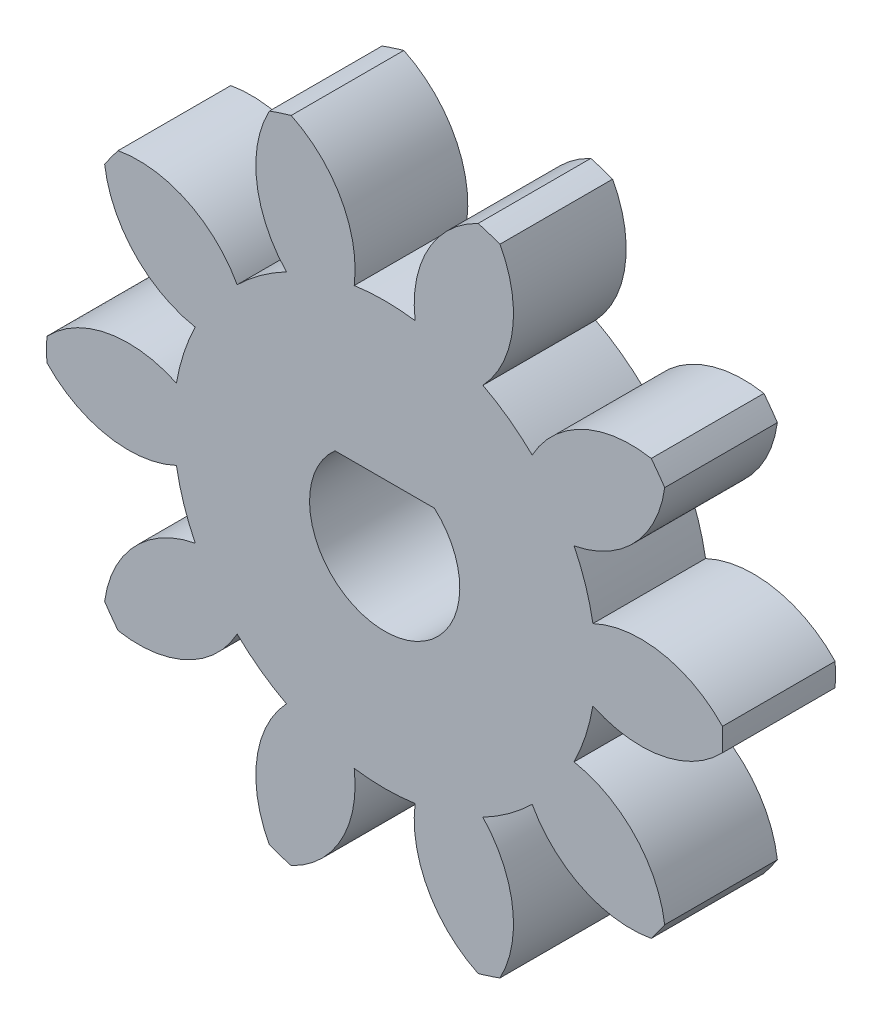
SolidWorks part; units mm, degrees
ref_plane "Front Plane" through (0, 0, 0) normal (0, 0, 1) x (1, 0, 0)
ref_plane "Top Plane" through (0, 0, 0) normal (0, 1, 0) x (1, 0, 0)
ref_plane "Right Plane" through (0, 0, 0) normal (1, 0, 0) x (0, 0, -1)
sketch "Sketch1" plane through (0, 0, 0) normal (0, 0, 1) x (1, 0, 0)
  circle A0 centre (0, 0) radius 9
  dimension "D1" = 18
extrude "Boss-Extrude1" add sketch "Sketch1" along normal blind 3
sketch "Sketch2" plane through (0, 0, 3) normal (0, 0, 1) x (1, 0, 0)
  line L0 (0, 0) -> (0, 29.4136) construction
  line L1 (0, 0) -> (-6.8576, 21.1056) construction
  line L3 (-2.2889, 7.0444) -> (-1.1684, 7.4084) construction
  circle A0 centre (0, 0) radius 5.625 construction
  circle A1 centre (0, 0) radius 7.0477 construction
  circle A2 centre (0, 0) radius 7.5 construction
  arc A4 (-0.8106, 5.5663) -> (0.8106, 5.5663) centre (0, 0) cw
  arc A5 (-2.4893, 8.6489) -> (2.4893, 8.6489) centre (0, 0) cw
  circle A6 centre (0, 0) radius 9 construction
  arc A7 (-2.4893, 8.6489) -> (-0.8106, 5.5663) centre (-3.7867, 5.944) cw
  arc A8 (2.4893, 8.6489) -> (0.8106, 5.5663) centre (3.7867, 5.944) ccw
  point P22 (0, 9)
  dimension "D1" = 11.25
  dimension "D2" = 14.0954
  dimension "D3" = 15
  dimension "D6" = 3
  dimension "D4" = 18
  dimension "D5" = 1.1781
extrude "Cut-Extrude1" cut sketch "Sketch2" against normal through all contours A8 A4 A7 A5
pattern_circular "CirPattern2" count 10 over 360 about axis through (0, 0, 0) along (0, 0, 1) of "Cut-Extrude1"
sketch "Sketch3" [suppressed] plane through (0, 0, 0) normal (0, 0, -1) x (-1, 0, 0)
  line L0 (0, 20.625) -> (0, -20.625) construction
  line L1 (0, 2.5) -> (-5.5785, 14.0839)
  line L2 (0, 2.5) -> (5.5785, 14.0839)
  arc A0 (0.6079, 20.616) -> (-0.6079, 20.616) centre (0, 0) ccw construction
  arc A1 (-0.6079, -20.616) -> (0.6079, -20.616) centre (0, 0) ccw construction
  arc A3 (5.5785, 14.0839) -> (-5.5785, 14.0839) centre (0, 0) ccw
  dimension "D1" = 2.5
  dimension "D2" = 4.2857
  dimension "D3" = 120
extrude "Cut-Extrude2" [suppressed] cut sketch "Sketch3" against normal through all
fillet "Fillet1" [suppressed] radius 1
pattern_circular "CirPattern3" [suppressed] count 6 over 360
sketch "Sketch5" plane through (0, 0, 3) normal (0, 0, 1) x (1, 0, 0)
  line L0 (-1.3229, 1.5) -> (1.3229, 1.5)
  arc A0 (-1.3229, 1.5) -> (1.3229, 1.5) centre (0, 0) ccw
  point P4 (0, 1.5)
  dimension "D1" = 2
  dimension "D2" = 1.5
extrude "Cut-Extrude3" cut sketch "Sketch5" against normal through all
equation "\"module\"= 1.5"
equation "\"teeth\"= 10"
equation "\"pressureAngle\"= 20deg"
equation "\"gearThickness\"= 3"
equation "\"addendumFactor\"= 1"
equation "\"dedendumFactor\"= 1.25"
equation "\"pitch\"= 1 / \"module\""
equation "\"pitchDiameter\"= \"teeth\" / \"pitch\""
equation "\"addendum\"= \"addendumFactor\" / \"pitch\""
equation "\"dedendum\"= \"dedendumFactor\" / \"pitch\""
equation "\"D1@Sketch1\"= \"pitchDiameter\" + 2 * \"addendum\""
equation "\"D1@Boss-Extrude1\"=\"gearThickness\""
equation "\"D1@Sketch2\"=\"pitchDiameter\" - 2 * \"dedendum\""
equation "\"D2@Sketch2\"=\"pitchDiameter\" * cos ( \"pressureAngle\" )"
equation "\"D3@Sketch2\"= \"pitchDiameter\""
equation "\"D4@Sketch2\"= 180 / \"teeth\""
equation "\"D6@Sketch2\"=\"pitchDiameter\" / 5"
equation "\"D5@Sketch2\"=PI/2/\"pitch\"/2"
equation "\"D1@CirPattern2\"=\"teeth\""
equation "\"D3@Sketch3\"=360 / ((\"teeth\" / 5)+1)"
equation "\"D2@Sketch3\"= \"pitchDiameter\" /3.5"
